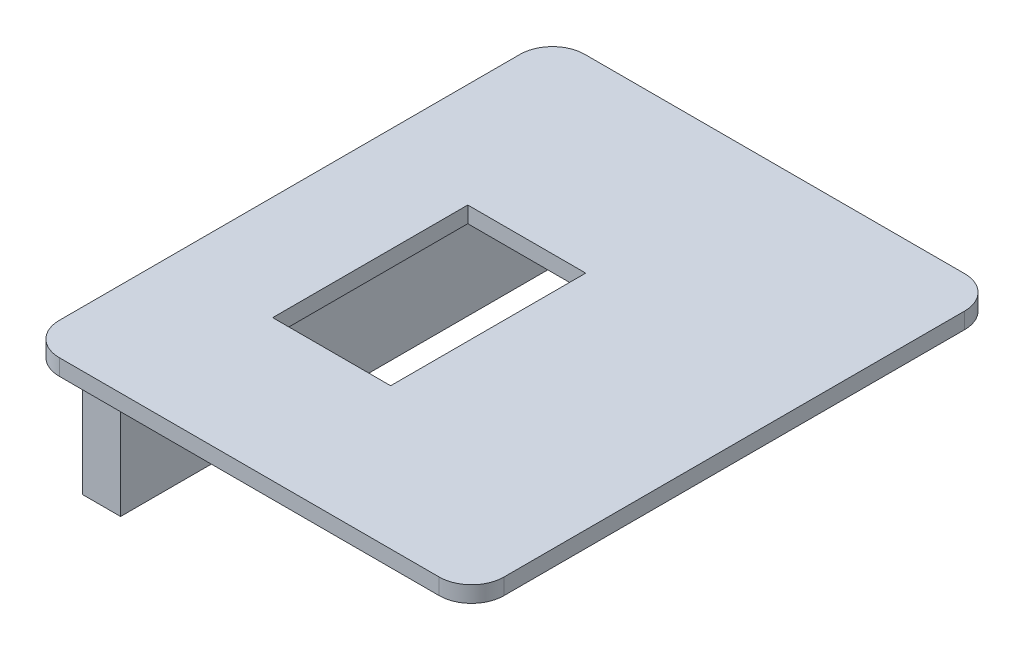
SolidWorks part; units mm, degrees
ref_plane "前视基准面" through (0, 0, 0) normal (0, 0, 1) x (1, 0, 0)
ref_plane "上视基准面" through (0, 0, 0) normal (0, 1, 0) x (1, 0, 0)
ref_plane "右视基准面" through (0, 0, 0) normal (1, 0, 0) x (0, 0, -1)
sketch "草图1" plane through (0, 0, 0) normal (0, 1, 0) x (1, 0, 0)
  line L1 (-23.5, -32.5) -> (23.5, -32.5)
  line L2 (-27.5, -28.5) -> (-27.5, 28.5)
  line L3 (-23.5, 32.5) -> (23.5, 32.5)
  line L4 (27.5, -28.5) -> (27.5, 28.5)
  line L5 (-27.5, -32.5) -> (27.5, 32.5) construction
  line L6 (-27.5, 32.5) -> (27.5, -32.5) construction
  line L7 (-14.5918, 9.1199) -> (0, 9.1199)
  line L8 (-14.5918, 9.1199) -> (-14.5918, -15.0128)
  line L9 (-14.5918, -15.0128) -> (0, -15.0128)
  line L10 (0, 9.1199) -> (0, -15.0128)
  line L11 (-14.5918, 9.1199) -> (0, -15.0128) construction
  line L12 (-14.5918, -15.0128) -> (0, 9.1199) construction
  arc A0 (23.5, -32.5) -> (27.5, -28.5) centre (23.5, -28.5) ccw
  arc A1 (-27.5, 28.5) -> (-23.5, 32.5) centre (-23.5, 28.5) cw
  arc A2 (-23.5, -32.5) -> (-27.5, -28.5) centre (-23.5, -28.5) cw
  arc A3 (23.5, 32.5) -> (27.5, 28.5) centre (23.5, 28.5) cw
  point P0 (0, 0)
  point P18 (-7.2959, -2.9464)
  dimension "D3" = 4
  dimension "D1" = 55
  dimension "D2" = 65
extrude "凸台-拉伸1" add sketch "草图1" along normal blind 2
sketch "草图2" plane through (0, 0, 0) normal (0, -1, 0) x (1, 0, 0)
  line L1 (-25.8819, 27.2281) -> (-21.1919, 27.2281)
  line L2 (-25.8819, 27.2281) -> (-25.8819, -27.2281)
  line L3 (-25.8819, -27.2281) -> (-21.1919, -27.2281)
  line L4 (-21.1919, 27.2281) -> (-21.1919, -27.2281)
  line L5 (-25.8819, 27.2281) -> (-21.1919, -27.2281) construction
  line L6 (-25.8819, -27.2281) -> (-21.1919, 27.2281) construction
  point P0 (-23.5369, 0)
extrude "凸台-拉伸2" add sketch "草图2" along normal blind 16.5
